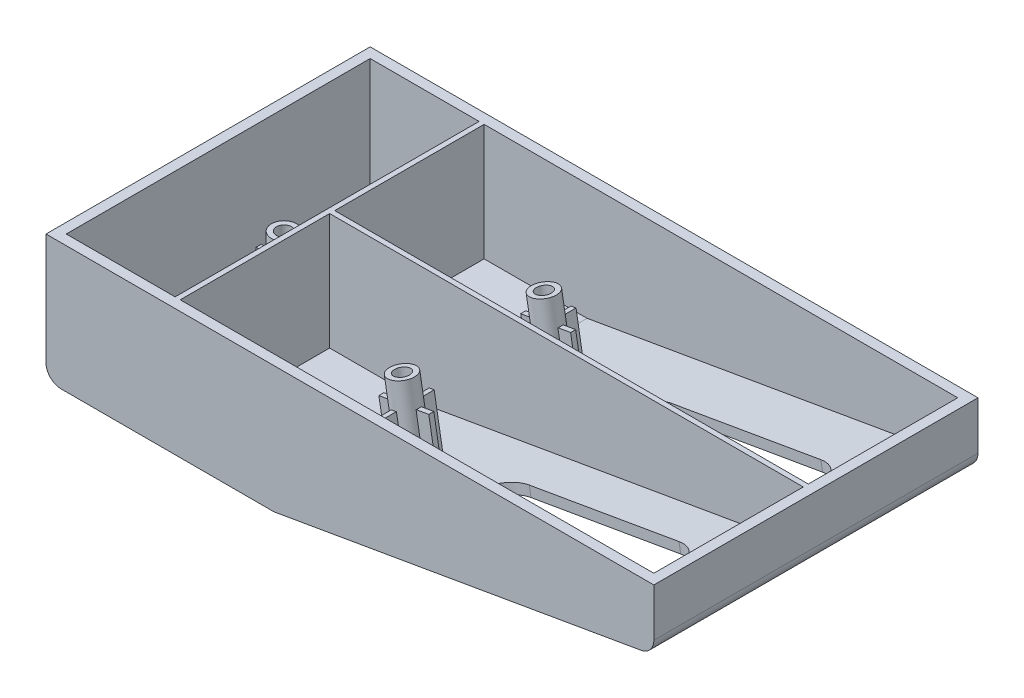
SolidWorks part; units mm, degrees
ref_plane "Front Plane" through (0, 0, 0) normal (0, 0, 1) x (1, 0, 0)
ref_plane "Top Plane" through (0, 0, 0) normal (0, 1, 0) x (1, 0, 0)
ref_plane "Right Plane" through (0, 0, 0) normal (1, 0, 0) x (0, 0, -1)
sketch "Sketch1" plane through (0, 0, 0) normal (0, 0, 1) x (1, 0, 0)
  line L0 (3, 0) -> (45, 0)
  line L1 (45, 0) -> (117.5124, 12.5688)
  line L2 (120, 15.5247) -> (120, 25)
  line L4 (0, 25) -> (0, 3)
  arc A0 (117.5124, 12.5688) -> (120, 15.5247) centre (117, 15.5247) ccw
  arc A1 (3, 0) -> (0, 3) centre (3, 3) cw
  point P8 (120, 13)
  point P11 (0, 0)
  dimension "D5" = 3
  dimension "D1" = 45
  dimension "D2" = 120
  dimension "D3" = 12
  dimension "D4" = 25
  dimension "D6" = 75
extrude "Extrude-Thin2" add sketch "Sketch1" along normal blind 64 thin thin type one direction reverse wall 2
sketch "Sketch2" plane through (0, 0, 0) normal (0, 0, 1) x (1, 0, 0)
  line L0 (2, 25) -> (118, 25)
rib "Rib1" sketch "Sketch2" sketch "Sketch2" thickness 2 parameters "D1"=2
ref_plane "Plane1" through (0, 0, 62) normal (0, 0, 1) x (1, 0, 0)
sketch "Sketch3" plane through (0, 0, 62) normal (0, 0, 1) x (1, 0, 0)
  line L0 (2, 25) -> (118, 25)
rib "Rib2" sketch "Sketch3" sketch "Sketch3" thickness 2 parameters "D1"=2
ref_plane "Plane2" through (0, 0, 32) normal (0, 0, -1) x (-1, 0, 0)
ref_plane "Plane3" through (24, 0, 0) normal (1, 0, 0) x (0, 0, -1)
sketch "Sketch8" plane through (0.971, -5.6019, 0) normal (-0.1708, 0.9853, 0) x (0.9853, 0.1708, 0)
  line L0 (72.5066, -18) -> (102.5066, -18) construction
  line L1 (72.5066, -13) -> (102.5066, -13)
  line L2 (72.5066, -23) -> (102.5066, -23)
  line L3 (72.5066, -46) -> (102.5066, -46) construction
  line L4 (72.5066, -41) -> (102.5066, -41)
  line L5 (72.5066, -51) -> (102.5066, -51)
  line L6 (122.5066, -64) -> (122.5066, 0) construction
  line L7 (4.2697, 0) -> (122.5066, 0) construction
  line L8 (4.2697, -64) -> (122.5066, -64) construction
  arc A0 (72.5066, -13) -> (72.5066, -23) centre (72.5066, -18) ccw
  arc A1 (102.5066, -23) -> (102.5066, -13) centre (102.5066, -18) ccw
  arc A2 (72.5066, -41) -> (72.5066, -51) centre (72.5066, -46) ccw
  arc A3 (102.5066, -51) -> (102.5066, -41) centre (102.5066, -46) ccw
  point P2 (87.5066, -18)
  point P7 (87.5066, -46)
  dimension "D2" = 5
  dimension "D4" = 5
  dimension "D1" = 20
  dimension "D3" = 20
  dimension "D5" = 30
  dimension "D6" = 30
  dimension "D7" = 18
  dimension "D8" = 18
extrude "Cut-Extrude1" cut sketch "Sketch8" against normal blind 10
sketch "Sketch12" plane through (24, 0, 0) normal (1, 0, 0) x (0, 0, -1)
  line L0 (-62, 25) -> (-2, 25)
rib "Rib9" sketch "Sketch12" sketch "Sketch12" thickness 1 extrusion direction parallel to sketch draft on no parameters "D1"=1
sketch "Sketch13" plane through (0, 0, 32) normal (0, 0, -1) x (-1, 0, 0)
  line L0 (-118, 25) -> (-24.5, 25)
rib "Rib10" sketch "Sketch13" sketch "Sketch13" thickness 1 extrusion direction parallel to sketch draft on no parameters "D1"=1
sketch "Sketch14" plane through (0, 2, 0) normal (0, 1, 0) x (1, 0, 0)
  line L0 (0, -64) -> (0, 0) construction
  line L1 (23.5, -32) -> (2, -32) construction
  line L2 (23.5, -62) -> (23.5, -2) construction
  line L3 (2, -62) -> (2, -2) construction
  circle A0 centre (15, -32) radius 2.5
  circle A1 centre (15, -32) radius 1.5
  dimension "D2" = 3
  dimension "D3" = 5
  dimension "D1" = 15
extrude "Boss-Extrude1" add sketch "Sketch14" along normal blind 15
sketch "Sketch15" plane through (0, 2, 0) normal (0, 1, 0) x (1, 0, 0)
  line L0 (12.5, -32) -> (17.5, -32) construction
  line L1 (14.5, -29.5505) -> (15.5, -29.5505)
  line L2 (14.5, -29.5505) -> (14.5, -27)
  line L3 (14.5, -27) -> (15.5, -27)
  line L4 (15.5, -29.5505) -> (15.5, -27)
  line L5 (15, -27) -> (15, -32) construction
  line L6 (12.5505, -32.5) -> (10, -32.5)
  line L7 (10, -32.5) -> (10, -31.5)
  line L8 (12.5505, -32.5) -> (12.5505, -31.5)
  line L9 (12.5505, -31.5) -> (10, -31.5)
  line L10 (15.5, -34.4495) -> (15.5, -37)
  line L11 (15.5, -37) -> (14.5, -37)
  line L12 (15.5, -34.4495) -> (14.5, -34.4495)
  line L13 (14.5, -34.4495) -> (14.5, -37)
  line L14 (17.4495, -31.5) -> (20, -31.5)
  line L15 (20, -31.5) -> (20, -32.5)
  line L16 (17.4495, -31.5) -> (17.4495, -32.5)
  line L17 (17.4495, -32.5) -> (20, -32.5)
  circle A0 centre (15, -32) radius 2.5 construction
  circle A1 centre (15, -32) radius 2.5 construction
  point P28 (15, -32)
  dimension "D1" = 5
  dimension "D2" = 1
  dimension "D3" = 4
extrude "Boss-Extrude2" add sketch "Sketch15" along normal blind 10
sketch "Sketch16" plane through (0.971, -5.6019, 0) normal (-0.1708, 0.9853, 0) x (0.9853, 0.1708, 0)
  line L0 (72.5066, -18) -> (44.5109, -18) construction
  line L1 (44.5109, -31.5) -> (44.5109, -2) construction
  line L2 (72.5066, -46) -> (44.5109, -46) construction
  line L3 (44.5109, -62) -> (44.5109, -32.5) construction
  circle A0 centre (54.683, -18) radius 2.5
  circle A1 centre (54.683, -18) radius 1.5
  circle A2 centre (54.683, -46) radius 2.5
  circle A3 centre (54.683, -46) radius 1.5
  dimension "D2" = 5
  dimension "D3" = 3
  dimension "D4" = 3
  dimension "D5" = 5
  dimension "D1" = 37
extrude "Boss-Extrude3" add sketch "Sketch16" along normal blind 15
sketch "Sketch17" plane through (0.971, -5.6019, 0) normal (-0.1708, 0.9853, 0) x (0.9853, 0.1708, 0)
  line L0 (53.183, -18) -> (56.183, -18) construction
  line L1 (54.183, -15.5505) -> (55.183, -15.5505)
  line L2 (54.183, -15.5505) -> (54.183, -13)
  line L3 (54.183, -13) -> (55.183, -13)
  line L4 (55.183, -15.5505) -> (55.183, -13)
  line L5 (57.1325, -17.5) -> (57.1325, -18.5)
  line L6 (57.1325, -17.5) -> (59.683, -17.5)
  line L7 (59.683, -17.5) -> (59.683, -18.5)
  line L8 (57.1325, -18.5) -> (59.683, -18.5)
  line L9 (55.183, -20.4495) -> (54.183, -20.4495)
  line L10 (55.183, -20.4495) -> (55.183, -23)
  line L11 (55.183, -23) -> (54.183, -23)
  line L12 (54.183, -20.4495) -> (54.183, -23)
  line L13 (52.2335, -18.5) -> (52.2335, -17.5)
  line L14 (52.2335, -18.5) -> (49.683, -18.5)
  line L15 (49.683, -18.5) -> (49.683, -17.5)
  line L16 (52.2335, -17.5) -> (49.683, -17.5)
  circle A0 centre (54.683, -18) radius 2.5 construction
  circle A1 centre (54.683, -18) radius 2.5 construction
  circle A2 centre (54.683, -18) radius 1.5 construction
  point P28 (54.683, -18)
  dimension "D1" = 1
  dimension "D2" = 5
  dimension "D3" = 4
extrude "Boss-Extrude4" add sketch "Sketch17" along normal blind 10
sketch "Sketch18" plane through (0.971, -5.6019, 0) normal (-0.1708, 0.9853, 0) x (0.9853, 0.1708, 0)
  line L0 (53.183, -46) -> (56.183, -46) construction
  line L1 (54.183, -43.5505) -> (55.183, -43.5505)
  line L2 (54.183, -43.5505) -> (54.183, -41)
  line L3 (54.183, -41) -> (55.183, -41)
  line L4 (55.183, -43.5505) -> (55.183, -41)
  line L5 (57.1325, -45.5) -> (57.1325, -46.5)
  line L6 (57.1325, -45.5) -> (59.683, -45.5)
  line L7 (59.683, -45.5) -> (59.683, -46.5)
  line L8 (57.1325, -46.5) -> (59.683, -46.5)
  line L9 (55.183, -48.4495) -> (54.183, -48.4495)
  line L10 (55.183, -48.4495) -> (55.183, -51)
  line L11 (55.183, -51) -> (54.183, -51)
  line L12 (54.183, -48.4495) -> (54.183, -51)
  line L13 (52.2335, -46.5) -> (52.2335, -45.5)
  line L14 (52.2335, -46.5) -> (49.683, -46.5)
  line L15 (49.683, -46.5) -> (49.683, -45.5)
  line L16 (52.2335, -45.5) -> (49.683, -45.5)
  circle A0 centre (54.683, -46) radius 2.5 construction
  circle A1 centre (54.683, -46) radius 1.5 construction
  circle A2 centre (54.683, -46) radius 1.5 construction
  circle A3 centre (54.683, -46) radius 2.5 construction
  point P28 (54.683, -46)
  dimension "D1" = 1
  dimension "D2" = 5
  dimension "D3" = 4
extrude "Boss-Extrude5" add sketch "Sketch18" along normal blind 10
